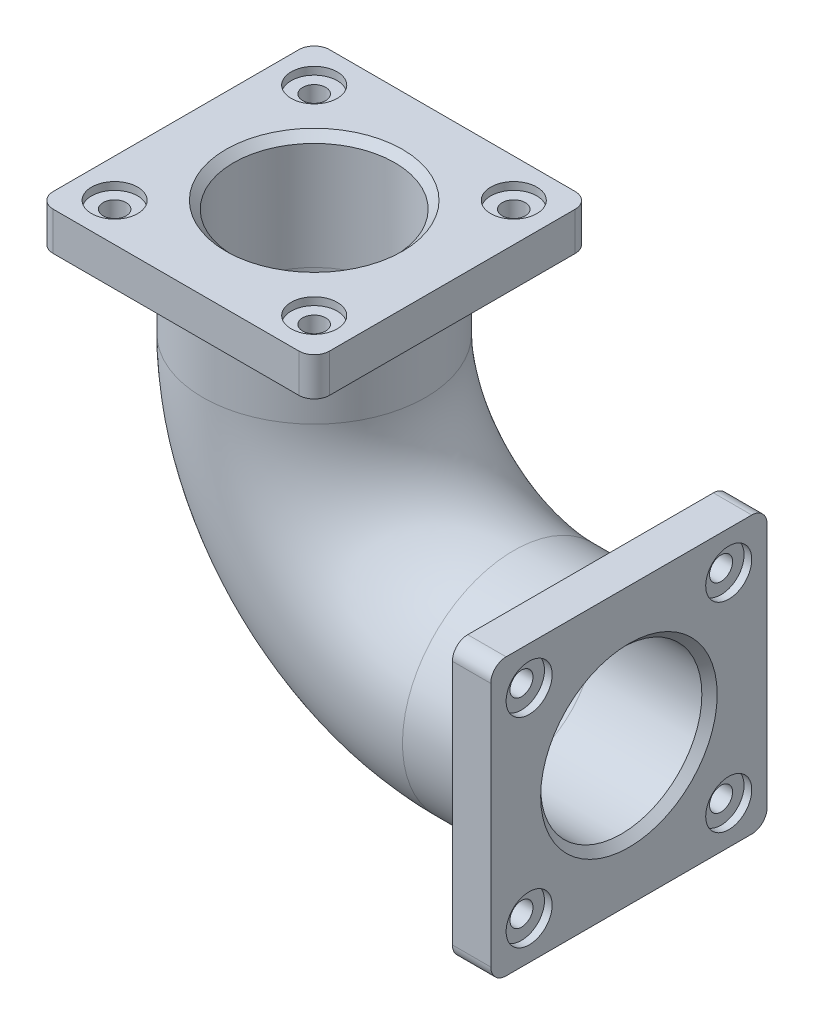
SolidWorks part; units mm, degrees
ref_plane "Front Plane" through (0, 0, 0) normal (0, 0, 1) x (1, 0, 0)
ref_plane "Top Plane" through (0, 0, 0) normal (0, 1, 0) x (1, 0, 0)
ref_plane "Right Plane" through (0, 0, 0) normal (1, 0, 0) x (0, 0, -1)
sketch "Sketch2" plane through (0, 0, 0) normal (0, 0, 1) x (1, 0, 0)
  line L0 (0, 0) -> (-150, 0)
  line L1 (-410, 260) -> (-410, 410)
  arc A0 (-150, 0) -> (-410, 260) centre (-150, 260) cw
  dimension "D2" = 260
  dimension "D1" = 150
sketch "Sketch3" plane through (0, 0, 0) normal (1, 0, 0) x (0, 0, -1)
  circle A0 centre (0, 0) radius 145
  dimension "D1" = 290
sweep "Sweep-Thin1" add profiles "Sketch3" path "Sketch2" parameters "D1"=40
sketch "Sketch4" plane through (0, 0, 0) normal (1, 0, 0) x (0, 0, -1)
  line L1 (-180, 180) -> (180, 180)
  line L2 (-180, 180) -> (-180, -180)
  line L3 (-180, -180) -> (180, -180)
  line L4 (180, 180) -> (180, -180)
  line L5 (-180, 180) -> (180, -180) construction
  line L6 (-180, -180) -> (180, 180) construction
  point P0 (0, 0)
  circle M4 centre (0, 0) radius 145
  dimension "D1" = 360
  dimension "D2" = 360
extrude "Boss-Extrude1" add sketch "Sketch4" against normal blind 50 contours L4 L1 L2 L3 M4
fillet "Fillet2" radius 20 4 edges at (-25, -180, -180) (-25, -180, 180) (-25, 180, -180) (-25, 180, 180)
sketch "Sketch5" plane through (0, 410, 0) normal (0, 1, 0) x (1, 0, 0)
  line L1 (-590, 180) -> (-230, 180)
  line L2 (-590, 180) -> (-590, -180)
  line L3 (-590, -180) -> (-230, -180)
  line L4 (-230, 180) -> (-230, -180)
  line L5 (-590, 180) -> (-230, -180) construction
  line L6 (-590, -180) -> (-230, 180) construction
  point P0 (-410, 0)
  circle M4 centre (-410, 0) radius 145
  dimension "D1" = 360
  dimension "D2" = 360
extrude "Boss-Extrude2" add sketch "Sketch5" against normal blind 50 contours L4 L1 L2 L3 M4
fillet "Fillet3" radius 20 4 edges at (-590, 385, 180) (-230, 385, 180) (-230, 385, -180) (-590, 385, -180)
sketch "Sketch6" plane through (0, 0, 0) normal (1, 0, 0) x (0, 0, -1)
  line L1 (-130, 130) -> (130, 130) construction
  line L2 (-130, 130) -> (-130, -130) construction
  line L3 (-130, -130) -> (130, -130) construction
  line L4 (130, 130) -> (130, -130) construction
  line L5 (-130, 130) -> (130, -130) construction
  line L6 (-130, -130) -> (130, 130) construction
  circle A0 centre (-130, 130) radius 30
  point P0 (0, 0)
  dimension "D1" = 60
  dimension "D2" = 260
  dimension "D3" = 260
extrude "Cut-Extrude1" cut sketch "Sketch6" against normal blind 10
sketch "Sketch7" plane through (-10, 0, 0) normal (1, 0, 0) x (0, 0, -1)
  circle A0 centre (-130, 130) radius 15
  dimension "D1" = 30
extrude "Cut-Extrude2" cut sketch "Sketch7" against normal up to next
pattern_circular "CirPattern1" count 4 over 360 about axis through (0, 0, 0) along (1, 0, 0) of "Cut-Extrude2", "Cut-Extrude1"
sketch "Sketch8" plane through (0, 410, 0) normal (0, 1, 0) x (1, 0, 0)
  line L0 (-410, 0) -> (-150, 0) construction
  line L1 (-540, 130) -> (-280, 130) construction
  line L2 (-540, 130) -> (-540, -130) construction
  line L3 (-540, -130) -> (-280, -130) construction
  line L4 (-280, 130) -> (-280, -130) construction
  line L5 (-540, 130) -> (-280, -130) construction
  line L6 (-540, -130) -> (-280, 130) construction
  circle A0 centre (-540, 130) radius 30
  point P0 (-410, 0)
  dimension "D3" = 60
  dimension "D1" = 260
  dimension "D2" = 260
extrude "Cut-Extrude3" cut sketch "Sketch8" against normal blind 10
sketch "Sketch9" plane through (0, 400, 0) normal (0, 1, 0) x (1, 0, 0)
  circle A0 centre (-540, 130) radius 15
  dimension "D1" = 30
extrude "Cut-Extrude4" cut sketch "Sketch9" against normal up to next
pattern_circular "CirPattern2" count 4 over 360 about axis through (-410, 0, 0) along (0, 1, 0) of "Cut-Extrude4", "Cut-Extrude3"
chamfer "Chamfer1" distance 10 angle 45 2 edges at (0, 0, -105) (-410, 410, -105)
